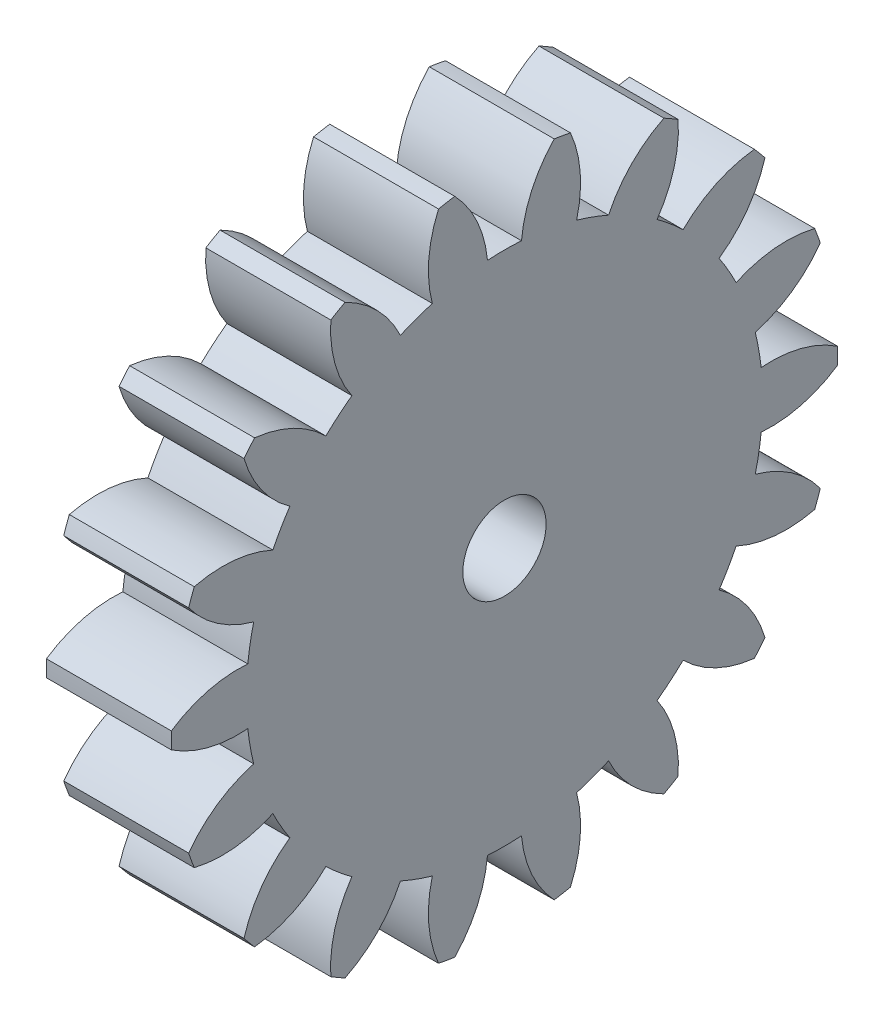
SolidWorks part; units mm, degrees
ref_plane "Plane1" through (0, 0, 0) normal (0, 0, 1) x (1, 0, 0)
ref_plane "Plane2" through (0, 0, 0) normal (0, 1, 0) x (1, 0, 0)
ref_plane "Plane3" through (0, 0, 0) normal (1, 0, 0) x (0, 0, -1)
sketch "HoldingSke" plane through (0, 0, 0) normal (0, 1, 0) x (1, 0, 0)
  line L0 (0, 0) -> (1.1888, -0.3863)
  line L1 (-15, 0) -> (100, 0) construction
  line L2 (0, 0) -> (-2.1039, 2.3779)
  line L3 (0, 0) -> (-11.863, 4.5341)
  line L4 (0, 0) -> (8.2133, 2.6687)
  line L5 (0, 0) -> (-46.8476, -17.4728)
  line L6 (0, 0) -> (-9.9476, -6.7116)
  line L7 (-2.1039, 2.3779) -> (8.6586, 51.2059)
  line L8 (-76.2, 54.61) -> (-75.9, 54.61)
  line L9 (-71.009, 38.7566) -> (-53.1078, 45.2721)
  line L10 (-76.2, 71.12) -> (104.1128, 71.12)
  line L11 (0, 0) -> (-12, 0)
  line L12 (-76.2, 101.6) -> (-76.17, 101.6)
  line L13 (24.9733, 27.94) -> (52.9518, 28.4284)
  line L14 (24.9733, 27.94) -> (24.9743, 27.94)
  line L15 (24.9733, 27.94) -> (100.4006, 29.5858)
  line L16 (-63.627, -0.8) -> (-12.827, -0.8)
  circle A0 centre (0, 0) radius 1
  circle A1 centre (0, 0) radius 6.199
  circle A2 centre (0, 0) radius 37.5
  circle A3 centre (0, 0) radius 1
  dimension "MHD" = 12.398
  dimension "Hub_dia" = 75
  dimension "Bore" = 2
  dimension "MBD" = 2
  dimension "Num_teeth" = 18
  dimension "Pitch" = 1.25
  dimension "Overall_len" = 50
  dimension "Show_teeth" = 18
  dimension "Thickness" = 12
  dimension "OAL" = 50.0001
  dimension "T_dim" = 0.3
  dimension "Ap" = 20
  dimension "H" = 19.05
  dimension "Pitch_radius" = 180.3128
  dimension "Width" = 12
  dimension "Backlash" = 0.03
  dimension "Addendum_fac" = 1
  dimension "Dedendum_fac" = 1.25
  dimension "Clearance_fac" = 0.25
  dimension "Dedendum_add" = 0.001
  dimension "Module" = 0.8
sketch "BasProSke" plane through (0, 0, 0) normal (0, 1, 0) x (1, 0, 0)
  line L0 (-10, 0) -> (60, 0) construction
  line L1 (0, 0) -> (0, 8)
  line L2 (0, 0) -> (12, 0)
  line L3 (12, 0) -> (12, 8)
  line L4 (12, 8) -> (0, 8)
  dimension "Thickness" = 12
  dimension "Diameter" = 16
revolve "Base-Revolve" add sketch "BasProSke" angle 360 about L0
sketch "TooCutSke" plane through (0, 0, 0) normal (1, 0, 0) x (0, 0, -1)
  line L1 (0, 0) -> (0, 107) construction
  line L2 (0, 0) -> (-0.68, 7.1678) construction
  line L3 (0, 0) -> (-2.4925, 14.1359) construction
  line L4 (-0.68, 7.1678) -> (-1.2463, 7.068) construction
  arc A0 (0.4079, 6.1856) -> (-0.4079, 6.1856) centre (0, 0) ccw
  arc A1 (1.2158, 7.9328) -> (-1.2158, 7.9328) centre (0, 0) ccw
  circle A2 centre (0, 0) radius 7.2 construction
  circle A3 centre (0, 0) radius 6.7658 construction
  arc A4 (-0.4079, 6.1856) -> (-1.2158, 7.9328) centre (-3.2756, 5.92) ccw
  arc A5 (1.2158, 7.9328) -> (0.4079, 6.1856) centre (3.2756, 5.92) ccw
  dimension "Root_dia" = 12.398
  dimension "Overcut_dia" = 16.0508
  dimension "Pitch_dia" = 14.4
  dimension "Base_dia" = 13.5316
  dimension "Flank_rad" = 2.88
  dimension "Half_ang" = 10
  dimension "Half_CT" = 0.575
extrude "ToothCut" cut sketch "TooCutSke" along normal through all
fillet "Breaks" [suppressed] radius 0.016
fillet "RootFillets" [suppressed] radius 0.201
pattern_circular "TeethCuts" count 18 every 20 about axis through (-10, 0, 0) along (1, 0, 0) of "ToothCut", "RootFillets", "Breaks"
sketch "HubNeaOneSke" plane through (0, 0, 0) normal (-1, 0, 0) x (0, 0, 1)
  circle A0 centre (0, 0) radius 6.199
  dimension "Diameter" = 12.398
extrude "HubNearOne" [suppressed] add sketch "HubNeaOneSke" along normal blind 38.0001
sketch "HubNeaBotSke" plane through (0, 0, 0) normal (-1, 0, 0) x (0, 0, 1)
  circle A0 centre (0, 0) radius 6.199
  dimension "Diameter" = 12.398
extrude "HubNearBoth" [suppressed] add sketch "HubNeaBotSke" along normal blind 19
ref_plane "FarPln" through (12, 0, 0) normal (1, 0, 0) x (0, 0, -1)
sketch "HubFarSke" plane through (12, 0, 0) normal (1, 0, 0) x (0, 0, -1)
  circle A0 centre (0, 0) radius 6.199
  dimension "Diameter" = 12.398
extrude "HubFar" [suppressed] add sketch "HubFarSke" along normal blind 19
sketch "BorSke" plane through (0, 0, 0) normal (1, 0, 0) x (0, 0, -1)
  circle A0 centre (0, 0) radius 1
  dimension "Diameter" = 2
extrude "Bore" cut sketch "BorSke" along normal mid plane 100.0001
sketch "KeySke" plane through (0, 0, 0) normal (1, 0, 0) x (0, 0, -1)
  line L0 (-0.4, 0) -> (-0.4, 1.3)
  line L1 (-0.4, 1.3) -> (0.4, 1.3)
  line L2 (0.4, 1.3) -> (0.4, 0)
  line L3 (0, 0) -> (0, 34) construction
  line L4 (-0.4, 0) -> (0.4, 0)
  dimension "Offset" = 1.3
  dimension "Width" = 0.8
extrude "Keyway" [suppressed] cut sketch "KeySke" along normal mid plane 100.0001
pattern_circular "Keyway2" [suppressed] count 2 every 90 about axis through (-10, 0, 0) along (1, 0, 0)
sketch "Croquis1" plane through (0, 0, 0) normal (-1, 0, 0) x (0, 0, 1)
  line L1 (-8.8903, 8.9548) -> (8.8903, 8.9548)
  line L2 (-8.8903, 8.9548) -> (-8.8903, -8.9032)
  line L3 (-8.8903, -8.9032) -> (8.8903, -8.9032)
  line L4 (8.8903, 8.9548) -> (8.8903, -8.9032)
extrude "Cortar-Extruir1" cut sketch "Croquis1" against normal blind 9
equation "' \"Module@HoldingSke\" = 6.35"
equation "' \"Num_teeth@HoldingSke\" = 12"
equation "' \"Ap@HoldingSke\" =  20"
equation "' \"Ap@HoldingSke\" = 20"
equation "' \"Width@HoldingSke\" = 0.5 * 25.4"
equation "' \"Hub_dia@HoldingSke\"= 1 * 25.4"
equation "' \"Hub_dia@HoldingSke\" = 1 * 25.4"
equation "' \"Overall_len@HoldingSke\" = 1.0 * 25.4"
equation "' \"Bore@HoldingSke\" = 0.75 * 25.4"
equation "' \"T_dim@HoldingSke\" = 0.1 * 25.4"
equation "' \"Width@KeySke\" = 0.25 * 25.4"
equation "' \"Show_teeth@HoldingSke\" = 13"
equation "' \"Backlash@HoldingSke\" = 0.009 * 25.4"
equation "' \"Addendum_fac@HoldingSke\" = 1.0"
equation "' \"Dedendum_fac@HoldingSke\" = 1.25"
equation "' \"Dedendum_add@HoldingSke\" = 0.00005 * 25.4"
equation "' \"Clearance_fac@HoldingSke\" = 0.25"
equation "\"Pitch@HoldingSke\" = 1 / \"Module@HoldingSke\""
equation "\"Overcut_dia@TooCutSke\" = (\"Num_teeth@HoldingSke\" + 2 * \"Addendum_fac@HoldingSke\") / \"Pitch@HoldingSke\" + 0.002 * 25.4"
equation "\"Pitch_dia@TooCutSke\" = \"Num_teeth@HoldingSke\" / \"Pitch@HoldingSke\""
equation "\"Base_dia@TooCutSke\" = \"Num_teeth@HoldingSke\" / \"Pitch@HoldingSke\" * cos((\"Ap@HoldingSke\"  * 3.14159265 / 180))"
equation "\"Root_dia@TooCutSke\" = (\"Num_teeth@HoldingSke\" + 2) / \"Pitch@HoldingSke\" - 2 * (\"Addendum_fac@HoldingSke\" + \"Dedendum_fac@HoldingSke\") / \"Pitch@HoldingSke\" - \"Dedendum_add@HoldingSke\" * 2"
equation "\"Half_ang@TooCutSke\" = 180 / \"Num_teeth@HoldingSke\""
equation "\"Half_CT@TooCutSke\" = \"Num_teeth@HoldingSke\" / \"Pitch@HoldingSke\" * sin((3.14159265 / 2 / \"Num_teeth@HoldingSke\")) / 2 - 7 * \"Backlash@HoldingSke\" / 4"
equation "\"Flank_rad@TooCutSke\" = \"Num_teeth@HoldingSke\" / \"Pitch@HoldingSke\" / 5"
equation "\"Radius@RootFillets\" = \"Clearance_fac@HoldingSke\" / \"Pitch@HoldingSke\" + \"Dedendum_add@HoldingSke\""
equation "\"Break_rad@Breaks\" = 0.02 / \"Pitch@HoldingSke\""
equation "\"Thickness@HoldingSke\" = \"Width@HoldingSke\""
equation "\"OAL@HoldingSke\" = \"Thickness@HoldingSke\""
equation "\"MHD@HoldingSke\" = (\"Num_teeth@HoldingSke\" + 2) / \"Pitch@HoldingSke\" - 2 * (\"Addendum_fac@HoldingSke\" + \"Dedendum_fac@HoldingSke\")  / \"Pitch@HoldingSke\" - \"Dedendum_add@HoldingSke\" * 2"
equation "\"MBD@HoldingSke\" = (\"Num_teeth@HoldingSke\" + 2) / \"Pitch@HoldingSke\" - 2 * (\"Addendum_fac@HoldingSke\" + \"Dedendum_fac@HoldingSke\")  / \"Pitch@HoldingSke\" - \"Dedendum_add@HoldingSke\" * 2 - 0.002 * 25.4"
equation "\"MHD@HoldingSke\" = ((sgn( \"MHD@HoldingSke\" - \"Hub_dia@HoldingSke\" )-1)*( \"MHD@HoldingSke\" - \"Hub_dia@HoldingSke\" ))/-2+ \"Hub_dia@HoldingSke\""
equation "\"MBD@HoldingSke\" = ((sgn( \"MBD@HoldingSke\" - \"Bore@HoldingSke\" )-1)*( \"MBD@HoldingSke\" - \"Bore@HoldingSke\" ))/-2+ \"Bore@HoldingSke\""
equation "\"OAL@HoldingSke\" = ((sgn( \"OAL@HoldingSke\" - \"Overall_len@HoldingSke\" )+1)*( \"OAL@HoldingSke\" - \"Overall_len@HoldingSke\" ))/2 + \"Overall_len@HoldingSke\" + 0.000002 * 25.4"
equation "\"Num_teeth@TeethCuts\" = int( \"Show_teeth@HoldingSke\" ) + 1"
equation "\"Num_teeth@TeethCuts\" = ((sgn( \"Num_teeth@TeethCuts\" - \"Num_teeth@HoldingSke\" )-1)*( \"Num_teeth@TeethCuts\" - \"Num_teeth@HoldingSke\" ))/-2+ \"Num_teeth@HoldingSke\""
equation "\"Num_teeth@TeethCuts\" = ((sgn( \"Num_teeth@TeethCuts\" - 2.0)+1)*( \"Num_teeth@TeethCuts\" - 2.0))/2 +2.0"
equation "\"Angle@TeethCuts\" = 360.0 / \"Num_teeth@HoldingSke\""
equation "\"Diameter@BasProSke\" = (\"Num_teeth@HoldingSke\" + 2 * \"Addendum_fac@HoldingSke\") / \"Pitch@HoldingSke\""
equation "\"Thickness@BasProSke\"  = \"Thickness@HoldingSke\""
equation "' \"Fillet_rad@BasProSke\" =  \"Thickness@HoldingSke\" * 0.05"
equation "' \"Fillet_rad@BasProSke\" = \"Thickness@HoldingSke\" * 0.05"
equation "\"MHD@HoldingSke\" = ((sgn( \"MHD@HoldingSke\" - \"Root_dia@TooCutSke\" )-1)*( \"MHD@HoldingSke\" - \"Root_dia@TooCutSke\" ))/-2+ \"Root_dia@TooCutSke\""
equation "\"Diameter@HubNeaOneSke\" = \"MHD@HoldingSke\""
equation "\"Length@HubNearOne\" = \"OAL@HoldingSke\" - \"Thickness@BasProSke\""
equation "\"Diameter@HubNeaBotSke\" = \"MHD@HoldingSke\""
equation "\"Length@HubNearBoth\" = ( \"OAL@HoldingSke\" - \"Thickness@BasProSke\" ) / 2.0"
equation "\"Thickness@FarPln\" = \"Thickness@BasProSke\""
equation "\"Diameter@HubFarSke\" = \"MHD@HoldingSke\""
equation "\"Length@HubFar\" = ( \"OAL@HoldingSke\" - \"Thickness@BasProSke\" ) / 2.0"
equation "\"Diameter@BorSke\" = \"MBD@HoldingSke\""
equation "\"D1@Bore\" = \"OAL@HoldingSke\" * 2.0"
equation "\"D1@Keyway\" = \"OAL@HoldingSke\" * 2.0"
equation "\"Offset@KeySke\" = \"T_dim@HoldingSke\" + \"MBD@HoldingSke\" / 2.0"
